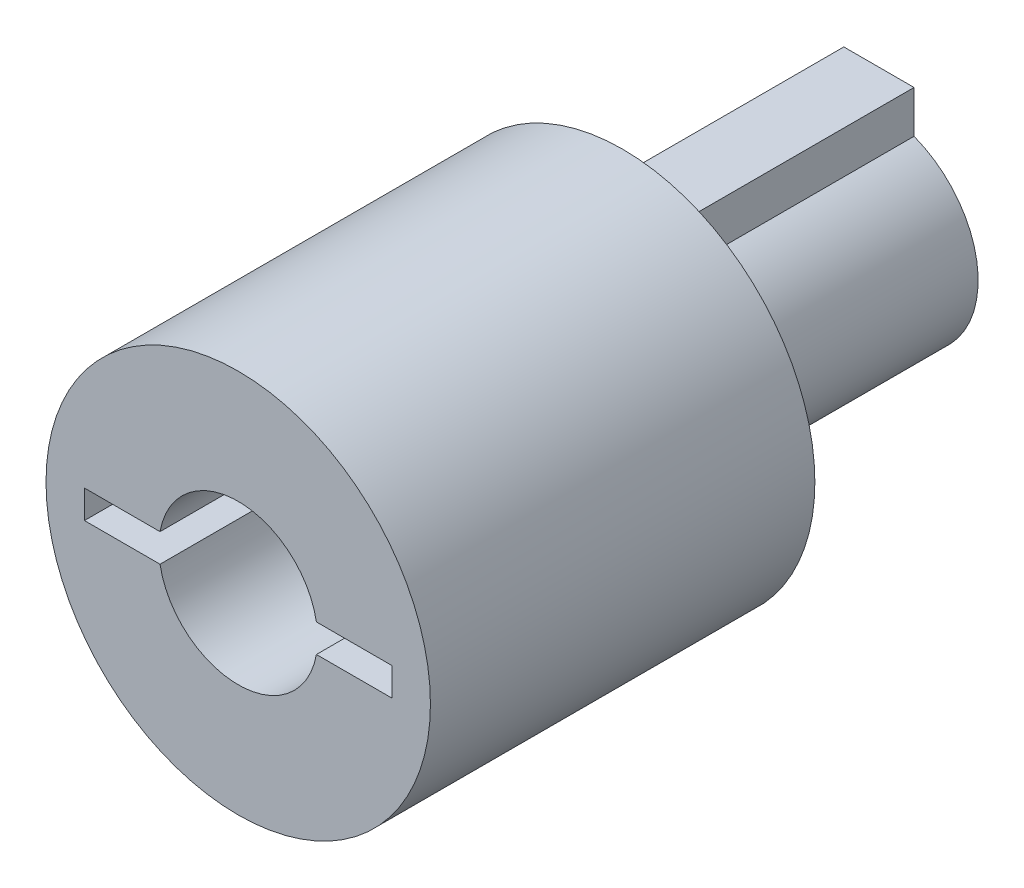
SolidWorks part; units mm, degrees
ref_plane "Front Plane" through (0, 0, 0) normal (0, 0, 1) x (1, 0, 0)
ref_plane "Top Plane" through (0, 0, 0) normal (0, 1, 0) x (1, 0, 0)
ref_plane "Right Plane" through (0, 0, 0) normal (1, 0, 0) x (0, 0, -1)
sketch "Sketch4" plane through (0, 0, 0) normal (0, 0, 1) x (1, 0, 0)
  line L12 (-1.37, 5.27) -> (-1.37, 3.6194)
  line L13 (1.37, 5.27) -> (-1.37, 5.27)
  line L14 (1.37, 3.6194) -> (1.37, 5.27)
  arc A6 (-1.37, 3.6194) -> (1.37, 3.6194) centre (0, 0) ccw
extrude "Boss-Extrude1" add sketch "Sketch4" against normal blind 10
sketch "Sketch5" plane through (0, 0, 0) normal (0, 0, 1) x (1, 0, 0)
  circle A0 centre (0, 0) radius 7.5
  dimension "D1" = 15
extrude "Boss-Extrude2" add sketch "Sketch5" along normal blind 15
sketch "Sketch8" plane through (0, 0, 15) normal (0, 0, 1) x (1, 0, 0)
  circle A0 centre (0, 0) radius 3.1
  dimension "D1" = 6.2
extrude "Cut-Extrude1" cut sketch "Sketch8" against normal blind 9
sketch "Sketch9" plane through (0, 0, 15) normal (0, 0, 1) x (1, 0, 0)
  line L0 (0, 0) -> (6, 0)
  line L1 (0, 0) -> (-6, 0)
  line L2 (0, 0.55) -> (6, 0.55)
  line L3 (0, 0.55) -> (-6, 0.55)
  line L4 (0, -0.55) -> (6, -0.55)
  line L5 (0, -0.55) -> (-6, -0.55)
  line L6 (-6, 0.55) -> (-6, -0.55)
  line L7 (6, -0.55) -> (6, 0.55)
  circle M9 centre (0, 0) radius 3.1
  dimension "D1" = 6
  dimension "D2" = 0.55
  dimension "D3" = 0.55
extrude "Cut-Extrude2" cut sketch "Sketch9" against normal blind 13 contours L2 L3 L1 L0 M9 | L3 L6 L1 M9 | L1 L6 L5 M9 | L5 L4 L0 L1 M9 | L4 L7 L0 M9 | L0 L7 L2 M9
